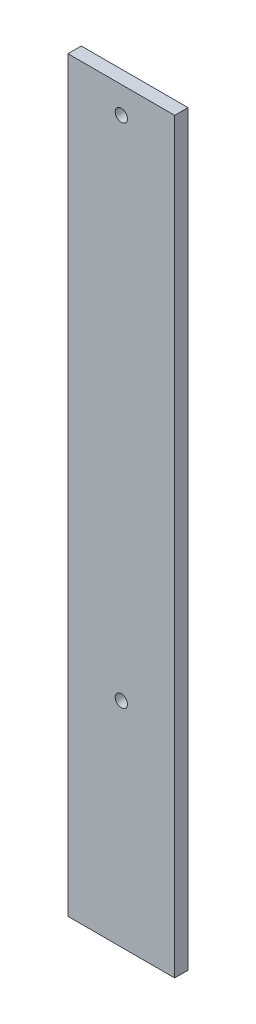
SolidWorks part; units mm, degrees
ref_plane "Front Plane" through (0, 0, 0) normal (0, 0, 1) x (1, 0, 0)
ref_plane "Top Plane" through (0, 0, 0) normal (0, 1, 0) x (1, 0, 0)
ref_plane "Right Plane" through (0, 0, 0) normal (1, 0, 0) x (0, 0, -1)
sketch "Sketch2" plane through (0, 0, 0) normal (0, 0, 1) x (1, 0, 0)
  line L0 (12.7, 177.8) -> (12.7, 0) construction
  line L1 (0, 0) -> (25.4, 0)
  line L2 (0, 0) -> (0, 177.8)
  line L3 (0, 177.8) -> (25.4, 177.8)
  line L4 (25.4, 0) -> (25.4, 177.8)
  circle A0 centre (12.7, 171.45) radius 1.4605
  circle A1 centre (12.7, 50.8) radius 1.4605
  dimension "D3" = 2.921
  dimension "D5" = 2.921
  dimension "D1" = 25.4
  dimension "D2" = 177.8
  dimension "D4" = 6.35
  dimension "D6" = 120.65
extrude "Boss-Extrude1" add sketch "Sketch2" along normal blind 3.175
